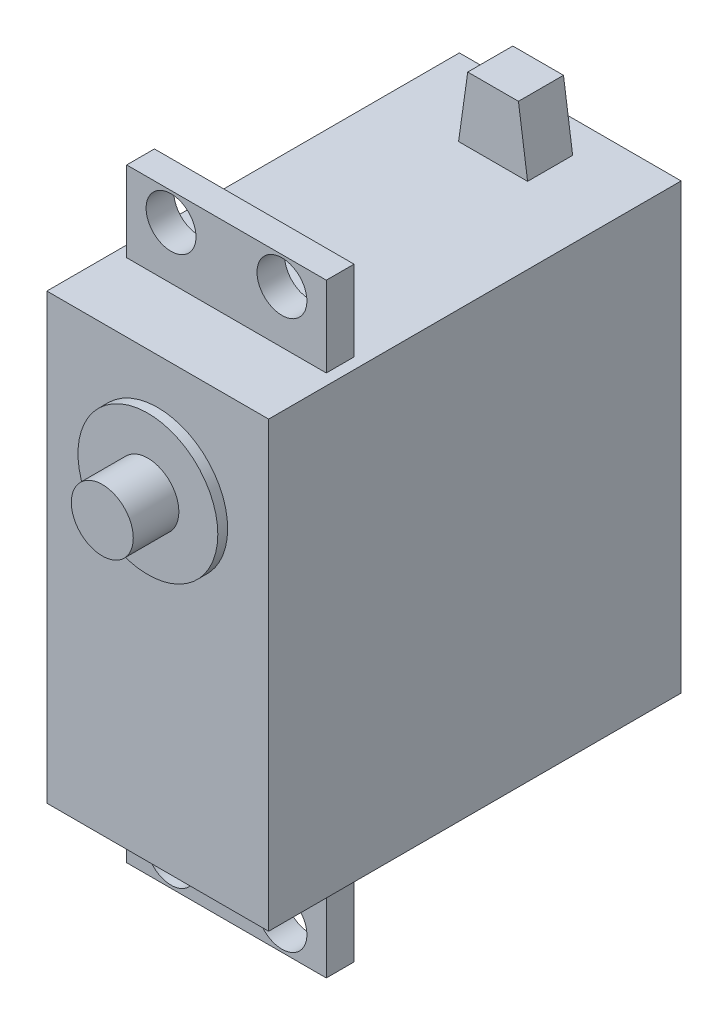
SolidWorks part; units mm, degrees
ref_plane "Front Plane" through (0, 0, 0) normal (0, 0, 1) x (1, 0, 0)
ref_plane "Top Plane" through (0, 0, 0) normal (0, 1, 0) x (1, 0, 0)
ref_plane "Right Plane" through (0, 0, 0) normal (1, 0, 0) x (0, 0, -1)
sketch "Sketch1" plane through (0, 0, 0) normal (0, 0, 1) x (1, 0, 0)
  line L1 (0, 40) -> (20, 40)
  line L2 (0, 40) -> (0, 0)
  line L3 (0, 0) -> (20, 0)
  line L4 (20, 40) -> (20, 0)
  dimension "D1" = 20
  dimension "D2" = 40
extrude "Boss-Extrude1" add sketch "Sketch1" along normal blind 8.7
sketch "Sketch2" plane through (0, 0, 0) normal (0, 0, -1) x (-1, 0, 0)
  line L0 (-20, 40) -> (0, 40) construction
  line L1 (-20, 40) -> (0, 40)
  line L2 (-20, 40) -> (-20, 0)
  line L3 (-20, 0) -> (0, 0)
  line L4 (0, 40) -> (0, 0)
  line L5 (-20, 0) -> (-20, 40) construction
  line L6 (0, 40) -> (0, 0) construction
extrude "Boss-Extrude2" add sketch "Sketch2" along normal blind 28.5
sketch "Sketch3" plane through (0, 0, 0) normal (0, 0, 1) x (1, 0, 0)
  line L0 (0, 0) -> (20, 0) construction
  line L1 (19, 0) -> (1, 0) construction
  line L2 (19, 0) -> (19, -7.25)
  line L3 (20, 40) -> (20, 0)
  line L4 (1, 0) -> (1, -7.25)
  line L5 (20, 40) -> (0, 40) construction
  line L6 (0, 40) -> (0, 0)
  line L7 (19, 47.25) -> (19, 40)
  line L8 (19, 40) -> (1, 40) construction
  line L9 (1, 47.25) -> (1, 40)
  line L10 (20, 0) -> (19, 0)
  line L11 (1, 0) -> (0, 0)
  line L12 (20, 40) -> (19, 40)
  line L13 (1, 40) -> (0, 40)
  line L14 (0, 40) -> (0, 0) construction
  line L15 (20, 0) -> (20, 40) construction
  line L19 (1, 47.25) -> (19, 47.25)
  line L20 (1, -7.25) -> (19, -7.25)
  line L24 (10, 47.25) -> (10, 44.75) construction
  line L25 (10, -7.25) -> (10, -4.75) construction
  line L28 (15, 44.75) -> (15, -4.75) construction
  line L29 (5, 44.75) -> (5, -4.75) construction
  line L30 (5, -4.75) -> (15, -4.75) construction
  line L31 (5, 44.75) -> (15, 44.75) construction
  circle A0 centre (5, -4.75) radius 2.25
  circle A1 centre (15, -4.75) radius 2.25
  circle A2 centre (5, 44.75) radius 2.25
  circle A3 centre (15, 44.75) radius 2.25
  dimension "D6" = 4.5
  dimension "D1" = 18
  dimension "D2" = 54.5
  dimension "D3" = 49.5
  dimension "D4" = 10
extrude "Boss-Extrude3" add sketch "Sketch3" along normal blind 2.5
sketch "Sketch4" plane through (0, 0, 8.7) normal (0, 0, 1) x (1, 0, 0)
  line L76 (0, 29.6) -> (20, 29.6) construction
  line L77 (0, 40) -> (0, 0) construction
  line L78 (20, 0) -> (20, 40) construction
  line L79 (5, 44.75) -> (15, 44.75) construction
  line L80 (20, 40) -> (0, 40) construction
  circle A0 centre (10, 29.6) radius 2.794
  circle A2 centre (5, 44.75) radius 2.25 construction
  circle A3 centre (15, 44.75) radius 2.25 construction
  dimension "D1" = 5.588
  dimension "D2" = 15.15
extrude "Boss-Extrude4" add sketch "Sketch4" along normal blind 5
sketch "Sketch9" plane through (0, 0, -28.5) normal (0, 0, -1) x (-1, 0, 0)
  line L0 (0, 40) -> (-20, 40) construction
  line L1 (-13.1115, 40) -> (-6.8885, 40)
  line L2 (-13.1115, 40) -> (-12.286, 45.842)
  line L3 (-12.286, 45.842) -> (-7.714, 45.842)
  line L4 (-6.8885, 40) -> (-7.714, 45.842)
  line L5 (-10, 40) -> (-10, 45.842) construction
  point P4 (-10, 40)
  dimension "D1" = 6.223
  dimension "D2" = 4.572
  dimension "D3" = 5.842
extrude "Boss-Extrude6" add sketch "Sketch9" against normal blind 6.9596
sketch "Sketch10" plane through (0, 0, 8.7) normal (0, 0, 1) x (1, 0, 0)
  circle A0 centre (10, 29.6) radius 6.3056
  circle A1 centre (10, 29.6) radius 2.794 construction
  dimension "D1" = 12.6111
extrude "Boss-Extrude7" add sketch "Sketch10" along normal blind 0.889
sketch "Sketch11" plane through (0, 0, -28.5) normal (0, 0, -1) x (-1, 0, 0)
  line L0 (-12.286, 45.842) -> (-7.714, 45.842)
  line L1 (-7.714, 45.842) -> (-6.8885, 40)
  line L2 (-6.8885, 40) -> (-13.1115, 40)
  line L3 (-13.1115, 40) -> (-12.286, 45.842)
extrude "Cut-Extrude1" cut sketch "Sketch11" against normal offset from surface (2.8956 mm away) 4.064 up to face at (10, 42.921, -21.5404)
sketch "Sketch12" plane through (0, 0, 2.5) normal (0, 0, 1) x (1, 0, 0)
  line L0 (5, -40.64) -> (5, 31.14) construction
  line L3 (19, 40) -> (19, 47.25) construction
  circle A3 centre (5, -4.75) radius 2.25 construction
  point P2 (5, -4.75)
  point P5 (0, 0)
  point P6 (0, 0)
